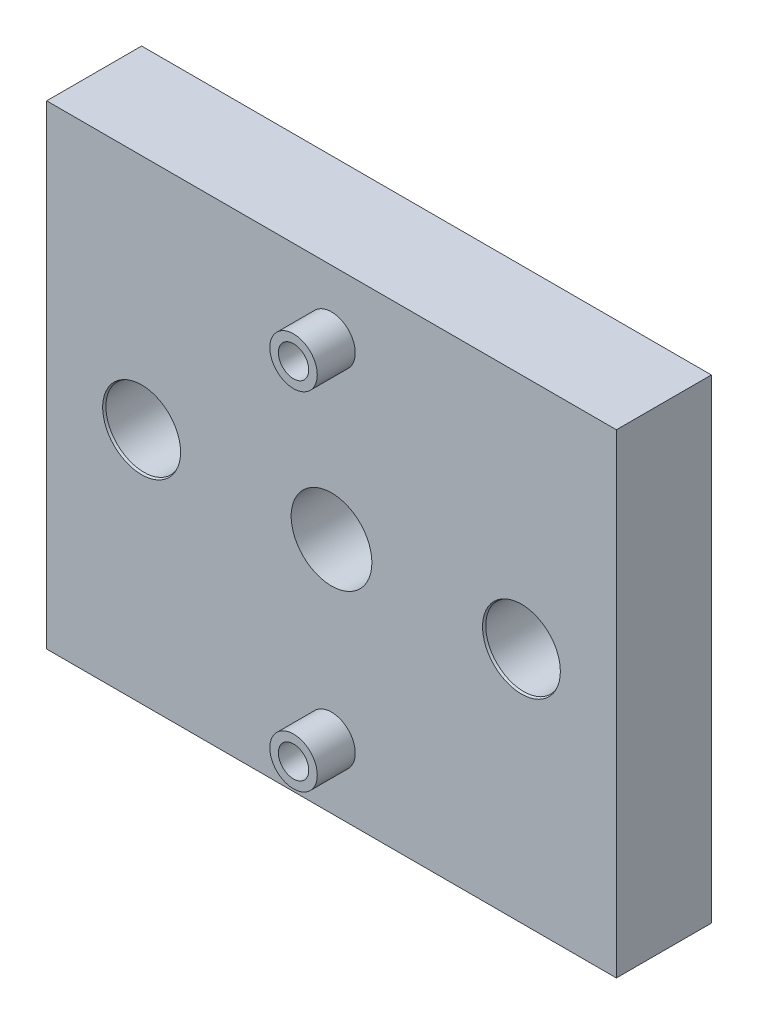
SolidWorks part; units mm, degrees
ref_plane "前视基准面" through (0, 0, 0) normal (0, 0, 1) x (1, 0, 0)
ref_plane "上视基准面" through (0, 0, 0) normal (0, 1, 0) x (1, 0, 0)
ref_plane "右视基准面" through (0, 0, 0) normal (1, 0, 0) x (0, 0, -1)
other "Configuration Table"
sketch "草图1" plane through (0, 0, 0) normal (0, 0, 1) x (1, 0, 0)
  line L1 (-30, -25) -> (30, -25)
  line L2 (-30, -25) -> (-30, 25)
  line L3 (-30, 25) -> (30, 25)
  line L4 (30, -25) -> (30, 25)
  line L5 (-30, -25) -> (30, 25) construction
  line L6 (-30, 25) -> (30, -25) construction
  point P0 (0, 0)
  dimension "D1" = 50
  dimension "D2" = 60
extrude "凸台-拉伸1" add sketch "草图1" along normal blind 10
hole_wizard "孔1" positions "草图2" profile "草图3" legacy
sketch "草图2" plane through (0, 0, 10) normal (0, 0, 1) x (1, 0, 0)
  point P0 (0, 0)
sketch "草图3" plane through (0, 0, 10) normal (1, 0, 0) x (0, -1, 0)
  line L0 (0, 0) -> (0, 20)
  line L1 (0, 20) -> (4.25, 20)
  line L2 (4.25, 20) -> (4.25, 0)
  line L3 (4.25, 0) -> (0, 0)
  line L4 (0, 110) -> (0, -10) construction
  dimension "直径" = 8.5
  dimension "深度" = 20
hole_wizard "孔2" positions "草图4" profile "草图5" legacy end condition through all
sketch "草图4" plane through (0, 0, 10) normal (0, 0, 1) x (1, 0, 0)
  point P0 (20, 0)
  point P2 (-20, 0)
  dimension "D1" = 20
  dimension "D2" = 20
sketch "草图5" plane through (20, 0, 10) normal (1, 0, 0) x (0, -1, 0)
  line L0 (0, 0) -> (0, 10)
  line L1 (0, 10) -> (4, 10)
  line L2 (4, 10) -> (4, 0.2414)
  line L3 (4, 0.2414) -> (4.1, 0)
  line L4 (4.1, 0) -> (0, 0)
  line L5 (0, -6.4453) -> (0, 115.525) construction
  line L6 (-4, 0.2414) -> (-4.1, 0) construction
  dimension "直径" = 8
  dimension "深度" = 10
  dimension "锥坑角度" = 45
  dimension "锥坑直径" = 8.2
sketch "草图9" plane through (0, 0, 10) normal (0, 0, 1) x (1, 0, 0)
  circle A0 centre (0, 18.25) radius 2.5
  circle A1 centre (0, -18.25) radius 2.5
  dimension "D1" = 5
  dimension "D2" = 5
  dimension "D3" = 18.25
  dimension "D4" = 18.25
extrude "凸台-拉伸3" add sketch "草图9" along normal blind 4
hole_wizard "孔3" positions "草图10" profile "草图11" legacy end condition through all
sketch "草图10" plane through (0, 0, 14) normal (0, 0, 1) x (1, 0, 0)
  point P0 (0, 18.25)
  point P3 (0, -18.25)
sketch "草图11" plane through (0, 18.25, 14) normal (1, 0, 0) x (0, -1, 0)
  line L0 (0, 0) -> (0, 14)
  line L1 (0, 14) -> (1.6, 14)
  line L2 (1.6, 14) -> (1.6, 0)
  line L3 (1.6, 0) -> (0, 0)
  line L4 (0, 110) -> (0, -10) construction
  dimension "直径" = 3.2
  dimension "深度" = 14
